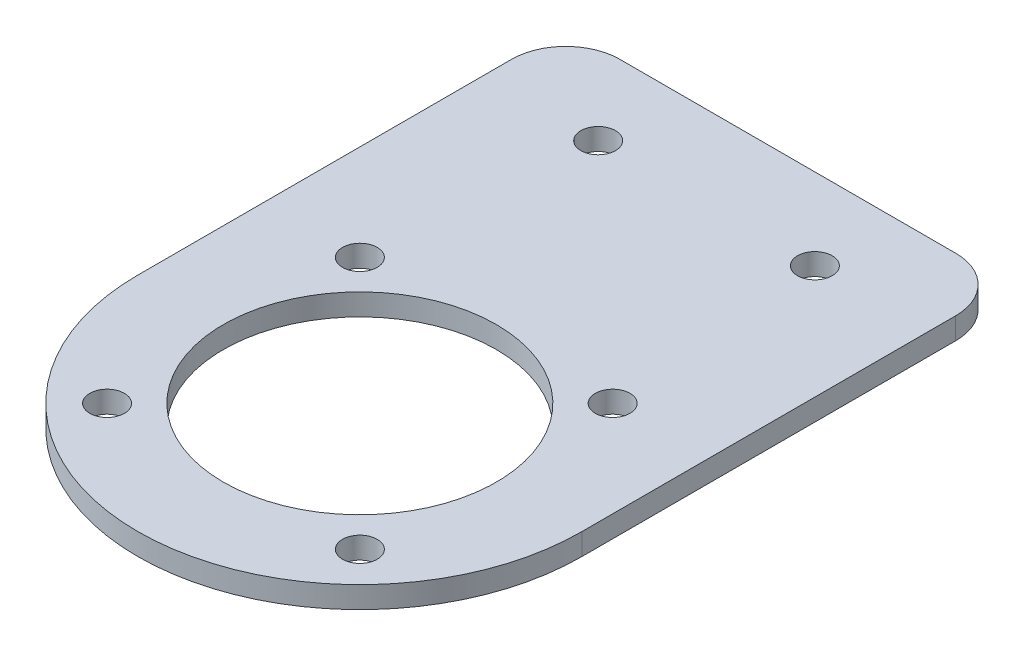
SolidWorks part; units mm, degrees
material "Carbon Fiber"
ref_plane "前视基准面" through (0, 0, 0) normal (0, 0, 1) x (1, 0, 0)
ref_plane "上视基准面" through (0, 0, 0) normal (0, 1, 0) x (1, 0, 0)
ref_plane "右视基准面" through (0, 0, 0) normal (1, 0, 0) x (0, 0, -1)
sketch "草图1" plane through (0, 0, 0) normal (0, 1, 0) x (1, 0, 0)
  line L0 (0, 0) -> (-8.9095, -8.9095) construction
  line L1 (-20.5, 0) -> (-20.5, 39.5)
  line L2 (20.5, 0) -> (20.5, 39.5)
  line L3 (20.5, 39.5) -> (-20.5, 39.5)
  line L4 (0, 39.5) -> (0, 24.5) construction
  line L5 (-20.5, 32) -> (-10, 32) construction
  line L6 (-10, 32) -> (10, 32) construction
  line L7 (10, 32) -> (20.5, 32) construction
  line L8 (0, 20.5) -> (0, -20.5) construction
  line L9 (0, 24.5) -> (0, 20.5) construction
  circle A1 centre (0, 0) radius 12.6
  circle A2 centre (0, 0) radius 20.5
  circle A3 centre (-11.6673, -11.6673) radius 1.6
  circle A4 centre (-10, 32) radius 1.6
  circle A5 centre (10, 32) radius 1.6
  circle A6 centre (-11.6673, 11.6673) radius 1.6
  circle A7 centre (11.6673, 11.6673) radius 1.6
  circle A8 centre (11.6673, -11.6673) radius 1.6
  circle A11 centre (0, 0) radius 16.5 construction
  point P17 (0, 32)
  point P31 (0, 0)
  dimension "D2" = 25.2
  dimension "D4" = 3.2
  dimension "D7" = 3.2
  dimension "D3" = 33
  dimension "D11" = 41
  dimension "D5" = 20
  dimension "D6" = 15
  dimension "D9" = 45
  dimension "D10" = 4
  dimension "D8" = 4
extrude "凸台-拉伸1" add sketch "草图1" along normal blind 2 contours A2 L2 L3 L1 A5 A4 | A2 A8 A7 A6 A3 A1
fillet "圆角1" radius 5 2 edges at (20.5, 1, -39.5) (-20.5, 1, -39.5)
